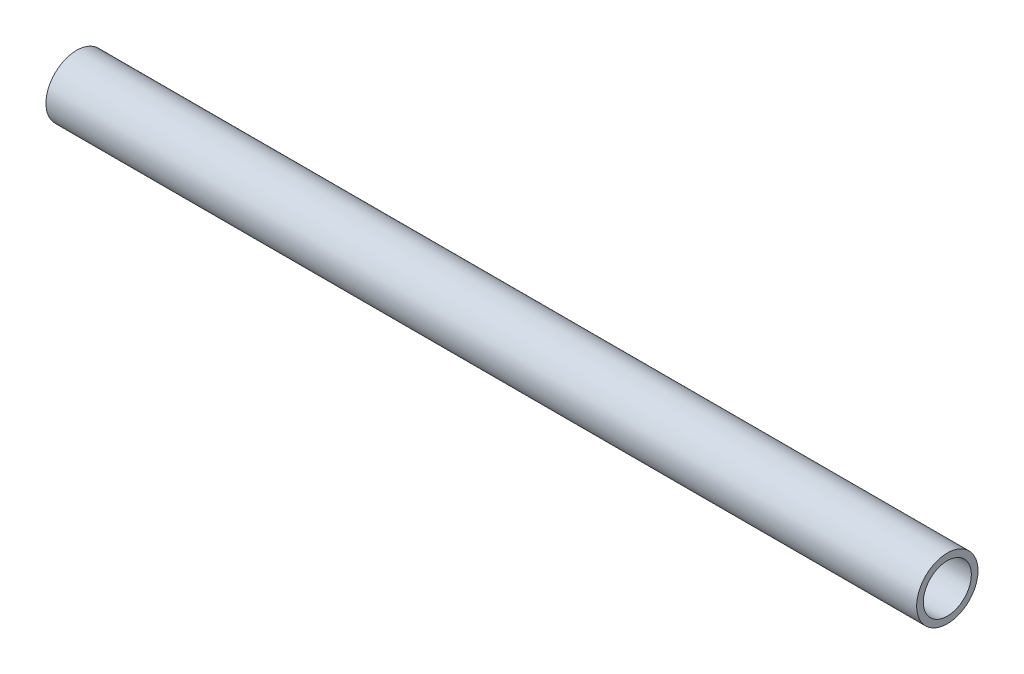
SolidWorks part; units mm, degrees
material "ASTM A106"
ref_plane "Front Plane" through (0, 0, 0) normal (0, 0, 1) x (1, 0, 0)
ref_plane "Top Plane" through (0, 0, 0) normal (0, 1, 0) x (1, 0, 0)
ref_plane "Right Plane" through (0, 0, 0) normal (1, 0, 0) x (0, 0, -1)
sketch "Sketch1" plane through (0, 0, 0) normal (1, 0, 0) x (0, 0, -1)
  circle A0 centre (0, 0) radius 13.35
  circle A1 centre (0, 0) radius 10.45
  dimension "D1" = 26.7
  dimension "D2" = 20.9
extrude "Boss-Extrude1" add sketch "Sketch1" along normal blind 378.9
